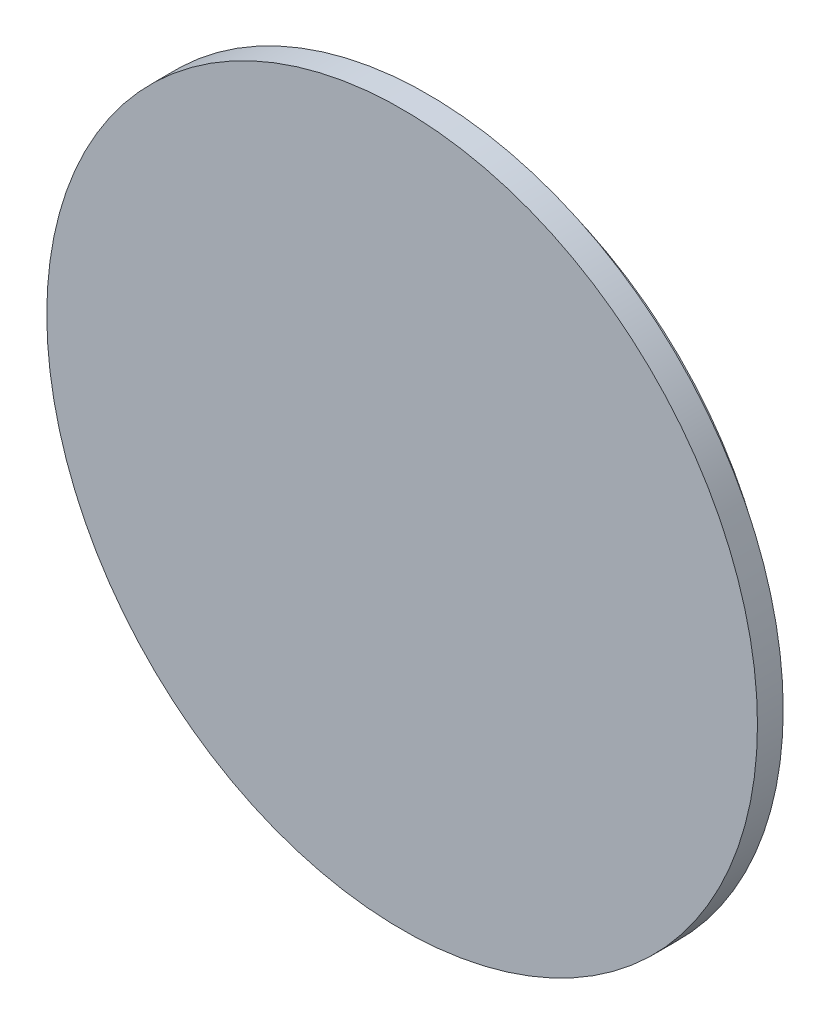
SolidWorks part; units mm, degrees
material "PET"
ref_plane "Front Plane" through (0, 0, 0) normal (0, 0, 1) x (1, 0, 0)
ref_plane "Top Plane" through (0, 0, 0) normal (0, 1, 0) x (1, 0, 0)
ref_plane "Right Plane" through (0, 0, 0) normal (1, 0, 0) x (0, 0, -1)
sketch "Sketch1" plane through (0, 0, 0) normal (0, 0, 1) x (1, 0, 0)
  circle A0 centre (0, 0) radius 34.5
  dimension "D1" = 69
extrude "Boss-Extrude1" add sketch "Sketch1" along normal blind 4.5
sketch "Sketch2" plane through (0, 0, 0) normal (0, 1, 0) x (1, 0, 0)
  line L1 (34.5, 0) -> (31.85, 0)
  line L2 (34.5, 0) -> (34.5, -2)
  line L3 (34.5, -2) -> (31.85, -2)
  line L4 (31.85, 0) -> (31.85, -2)
  dimension "D1" = 2.65
  dimension "D2" = 2
sketch "Sketch3" plane through (0, 0, 0) normal (0, 1, 0) x (1, 0, 0)
  line L0 (0, 0) -> (0, -4.5) construction
revolve "Cut-Revolve1" cut sketch "Sketch2" angle 360 about L0
sketch "Sketch4" plane through (0, 0, 0) normal (0, 1, 0) x (1, 0, 0)
  line L0 (31.85, 0) -> (-31.85, 0) construction
  line L1 (-0.775, 0) -> (0.775, 0)
  line L2 (-0.775, 0) -> (-0.775, -1.5)
  line L3 (-0.775, -1.5) -> (0.775, -1.5)
  line L4 (0.775, 0) -> (0.775, -1.5)
  line L5 (0, 200000) -> (0, -200004.5) construction
  dimension "D1" = 1.5
  dimension "D2" = 1.55
  dimension "D3" = 0.775
extrude "Cut-Extrude1" cut sketch "Sketch4" against normal through all both and the other way through all
sketch "Sketch6" plane through (0, 0, 0) normal (1, 0, 0) x (0, 0, -1)
  line L0 (0, -31.8406) -> (0, 31.8406) construction
  line L1 (200000, 0) -> (-200004.5, 0) construction
  line L2 (0, 0.775) -> (-1.5, 0.775)
  line L3 (0, 0.775) -> (0, -0.775)
  line L4 (0, -0.775) -> (-1.5, -0.775)
  line L5 (-1.5, 0.775) -> (-1.5, -0.775)
  dimension "D1" = 1.5
  dimension "D2" = 1.55
  dimension "D3" = 0.775
extrude "Cut-Extrude2" cut sketch "Sketch6" against normal through all
